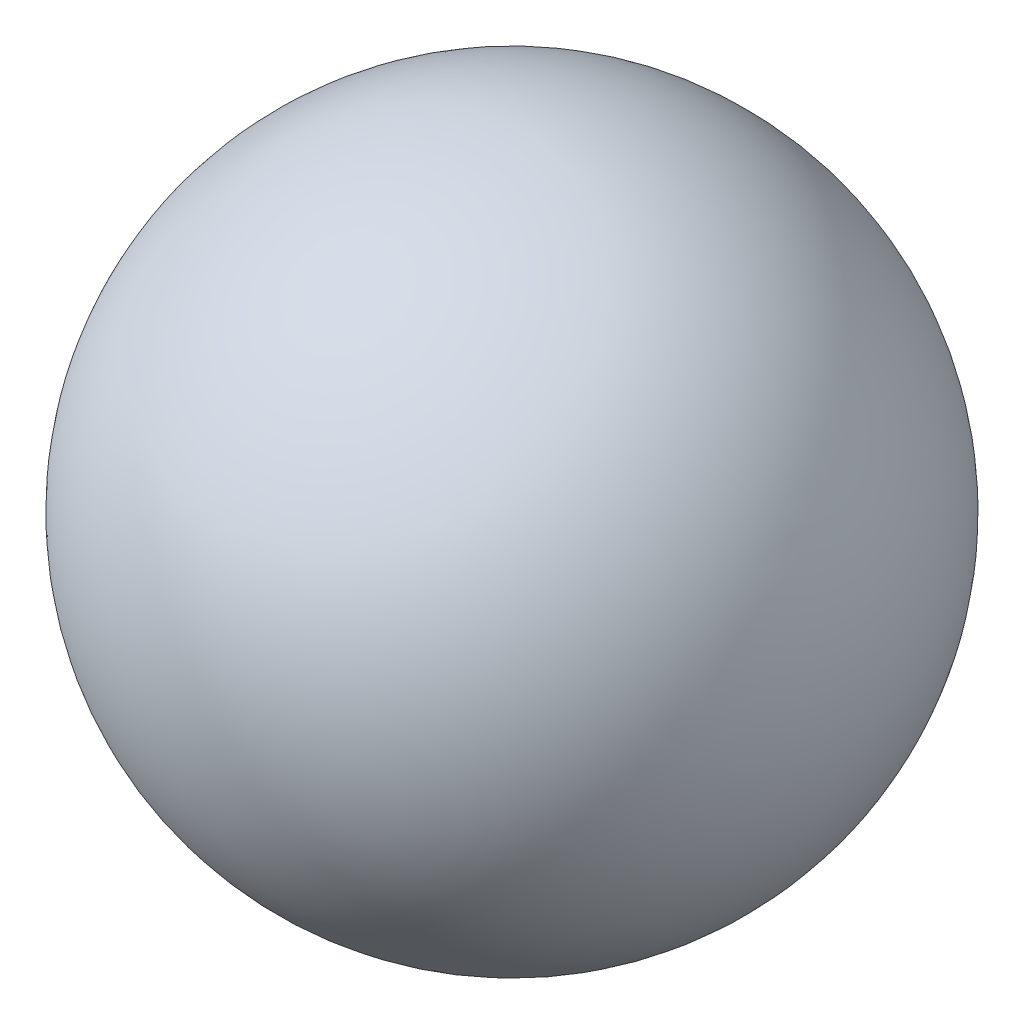
SolidWorks part; units mm, degrees
ref_plane "Piano frontale" through (0, 0, 0) normal (0, 0, 1) x (1, 0, 0)
ref_plane "Piano superiore" through (0, 0, 0) normal (0, 1, 0) x (1, 0, 0)
ref_plane "Piano destro" through (0, 0, 0) normal (1, 0, 0) x (0, 0, -1)
ref_plane "Piano1" through (0, 0, 0) normal (0, 0, 1) x (1, 0, 0)
sketch "Schizzo1" plane through (0, 0, 0) normal (0, 0, 1) x (1, 0, 0)
  line L0 (15.747, 66.25) -> (2.253, 66.25)
  line L1 (15.747, 66.25) -> (2.253, 66.25) construction
  arc A0 (2.253, 66.25) -> (15.747, 66.25) centre (9, 66.25) cw
revolve "Rivoluzione1" add sketch "Schizzo1" angle 360 about L1
